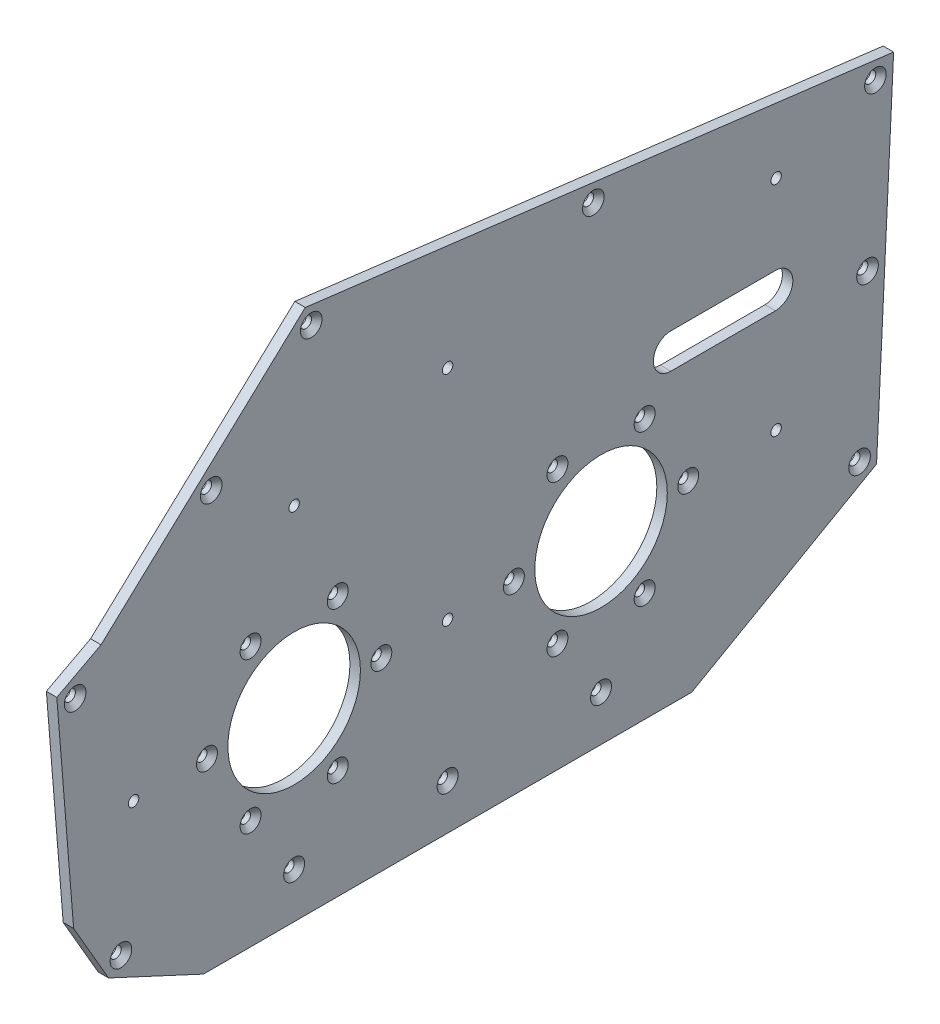
SolidWorks part; units mm, degrees
ref_plane "前视基准面" through (0, 0, 0) normal (0, 0, 1) x (1, 0, 0)
ref_plane "上视基准面" through (0, 0, 0) normal (0, 1, 0) x (1, 0, 0)
ref_plane "右视基准面" through (0, 0, 0) normal (1, 0, 0) x (0, 0, -1)
sketch "草图1" plane through (0, 0, 0) normal (1, 0, 0) x (0, 0, -1)
  line L0 (-82.7978, -47.6757) -> (57.2022, -47.6757)
  line L1 (-56.7978, 5.3243) -> (31.2022, 5.3243) construction
  line L2 (-12.7978, -47.6757) -> (-12.7978, 5.3243) construction
  line L3 (-81.3465, -44.5639) -> (329.9868, -44.5639) construction
  line L4 (-82.7978, -47.6757) -> (-110.0054, -35.0364)
  line L5 (-110.0054, -35.0364) -> (-120.0304, -17.7304)
  line L6 (-120.0304, -17.7304) -> (-124.8541, 42.0754)
  line L7 (-124.8541, 42.0754) -> (-112.1769, 48.7958)
  line L8 (-112.1769, 48.7958) -> (-53.6007, 103.2828)
  line L9 (-53.6007, 103.2828) -> (115.1062, 82.3551)
  line L10 (115.1062, 82.3551) -> (110.2084, -17.5249)
  line L11 (110.2084, -17.5249) -> (57.2022, -47.6757)
  line L12 (-56.7978, 5.3243) -> (-44.2978, 26.975) construction
  line L13 (-69.2978, 26.975) -> (-44.2978, 26.975) construction
  line L14 (31.2022, 5.3243) -> (43.7022, 26.975) construction
  line L15 (43.7022, 26.975) -> (18.7022, 26.975) construction
  line L16 (-12.7978, -47.6757) -> (-12.7978, -34.6757) construction
  line L17 (-12.7978, -34.6757) -> (-56.7978, -34.6757) construction
  line L18 (-12.7978, -34.6757) -> (31.2022, -34.6757) construction
  circle A0 centre (-56.7978, 5.3243) radius 19
  circle A1 centre (31.2022, 5.3243) radius 19
  circle A2 centre (-44.2978, 26.975) radius 1.5
  circle A3 centre (-69.2978, 26.975) radius 1.5
  circle A4 centre (-81.7978, 5.3243) radius 1.5
  circle A5 centre (-69.2978, -16.3263) radius 1.5
  circle A6 centre (-44.2978, -16.3263) radius 1.5
  circle A7 centre (-31.7978, 5.3243) radius 1.5
  circle A8 centre (43.7022, 26.975) radius 1.5
  circle A9 centre (56.2022, 5.3243) radius 1.5
  circle A10 centre (43.7022, -16.3263) radius 1.5
  circle A11 centre (18.7022, -16.3263) radius 1.5
  circle A12 centre (6.2022, 5.3243) radius 1.5
  circle A13 centre (18.7022, 26.975) radius 1.5
  circle A14 centre (-12.7978, -34.6757) radius 1.5
  circle A15 centre (-56.7978, -34.6757) radius 1.5
  circle A16 centre (31.2022, -34.6757) radius 1.5
  dimension "D2" = 38
  dimension "D3" = 38
  dimension "D23" = 3
  dimension "D26" = 6
  dimension "D27" = 3
  dimension "D29" = 3
  dimension "D32" = 3
  dimension "D33" = 3
  dimension "D1" = 140
  dimension "D4" = 88
  dimension "D5" = 53
  dimension "D6" = 155.083
  dimension "D7" = 30
  dimension "D8" = 145
  dimension "D9" = 20
  dimension "D10" = 154.528
  dimension "D11" = 60
  dimension "D12" = 113.317
  dimension "D13" = 14.3483
  dimension "D14" = 80
  dimension "D15" = 195
  dimension "D16" = 130
  dimension "D17" = 170
  dimension "D18" = 94.264
  dimension "D19" = 100
  dimension "D20" = 122.439
  dimension "D21" = 60.9814
  dimension "D22" = 25
  dimension "D25" = 25
  dimension "D28" = 13
  dimension "D30" = 44
  dimension "D31" = 44
  dimension "D24" = 6
extrude "凸台-拉伸1" add sketch "草图1" along normal blind 3
ref_plane "基准面1" through (13, 0, 0) normal (1, 0, 0) x (0, 0, -1)
sketch "草图2" plane through (13, 0, 0) normal (1, 0, 0) x (0, 0, -1)
  line L0 (-50.2042, 92.7848) -> (-106.3299, 40.5771)
  line L1 (-106.3299, 40.5771) -> (-114.3575, 36.3216)
  line L2 (-114.3575, 36.3216) -> (-110.2445, -14.6736)
  line L3 (-110.2445, -14.6736) -> (-102.9328, -27.2956)
  line L4 (-102.9328, -27.2956) -> (-80.5885, -37.6757)
  line L5 (-80.5885, -37.6757) -> (54.5571, -37.6757)
  line L6 (54.5571, -37.6757) -> (100.4894, -11.5486)
  line L7 (100.4894, -11.5486) -> (104.6636, 73.5738)
  line L8 (104.6636, 73.5738) -> (-50.2042, 92.7848)
  line L9 (-110.0054, -35.0364) -> (-82.7978, -47.6757)
  line L10 (-82.7978, -47.6757) -> (57.2022, -47.6757)
  line L11 (57.2022, -47.6757) -> (110.2084, -17.5249)
  line L12 (110.2084, -17.5249) -> (115.1062, 82.3551)
  line L13 (115.1062, 82.3551) -> (-53.6007, 103.2828)
  line L14 (-53.6007, 103.2828) -> (-112.1769, 48.7958)
  line L15 (-112.1769, 48.7958) -> (-124.8541, 42.0754)
  line L16 (-124.8541, 42.0754) -> (-120.0304, -17.7304)
  line L17 (-120.0304, -17.7304) -> (-110.0054, -35.0364)
  line L18 (-110.0054, -35.0364) -> (-82.7978, -47.6757)
  line L19 (-82.7978, -47.6757) -> (57.2022, -47.6757)
  line L20 (57.2022, -47.6757) -> (110.2084, -17.5249)
  line L21 (110.2084, -17.5249) -> (115.1062, 82.3551)
  line L22 (115.1062, 82.3551) -> (-53.6007, 103.2828)
  line L23 (-53.6007, 103.2828) -> (-112.1769, 48.7958)
  line L24 (-112.1769, 48.7958) -> (-124.8541, 42.0754)
  line L25 (-124.8541, 42.0754) -> (-120.0304, -17.7304)
  line L26 (-120.0304, -17.7304) -> (-110.0054, -35.0364)
  line L27 (-106.4691, -31.166) -> (-81.6932, -42.6757)
  line L28 (-81.6932, -42.6757) -> (55.8796, -42.6757)
  line L29 (55.8796, -42.6757) -> (105.3489, -14.5367)
  line L30 (105.3489, -14.5367) -> (109.8849, 77.9645)
  line L31 (109.8849, 77.9645) -> (-51.9024, 98.0338)
  line L32 (-51.9024, 98.0338) -> (-109.2534, 44.6864)
  line L33 (-109.2534, 44.6864) -> (-119.6058, 39.1985)
  line L34 (-119.6058, 39.1985) -> (-115.1374, -16.202)
  line L35 (-115.1374, -16.202) -> (-106.4691, -31.166)
  circle A0 centre (109.8849, 77.9645) radius 1.6
  circle A1 centre (105.3489, -14.5367) radius 1.6
  circle A3 centre (-106.4691, -31.166) radius 1.6
  circle A4 centre (-119.6058, 39.1985) radius 1.6
  circle A5 centre (-51.9024, 98.0338) radius 1.6
  circle A6 centre (28.9912, 87.9992) radius 1.6
  circle A7 centre (-80.5779, 71.3601) radius 1.6
  circle A8 centre (107.6169, 31.7139) radius 1.6
  dimension "D1" = 0
  dimension "D2" = 10
  dimension "D3" = 5
extrude "切除-拉伸1" cut sketch "草图2" against normal blind 77 contours L31 A6 | L31 A6 | L32 A5 L31 | L30 A0 L31 | L31 A0 L30 | L30 A8 | L30 A8 | L29 A1 L30 | L30 A1 L29 | L27 A3 L35 | L35 A3 L27 | L34 A4 L33 | L33 A4 L34 | L32 A7 | L32 A7
chamfer "倒角1" distance 1.5 angle 45 23 edges at (3, 77.9645, -111.4849) (3, 31.7139, -109.2169) (3, -14.5367, -106.9489) (3, 5.3243, -57.7022) (3, 5.3243, -7.7022) (3, -16.3263, -45.2022) (3, -16.3263, -20.2022) (3, -34.6757, -32.7022) (3, -34.6757, 11.2978) (3, -34.6757, 55.2978) (3, -31.166, 104.8691) (3, 71.3601, 78.9779) (3, 39.1985, 118.0058) (3, -16.3263, 67.7978) (3, -16.3263, 42.7978) (3, 5.3243, 30.2978) (3, 5.3243, 80.2978) (3, 26.975, 67.7978) (3, 26.975, 42.7978) (3, 26.975, -45.2022) (3, 26.975, -20.2022) (3, 87.9992, -30.5912) (3, 98.0338, 50.3024)
sketch "草图3" plane through (3, 0, 0) normal (1, 0, 0) x (0, 0, -1)
  line L0 (31.2022, 5.3243) -> (51.2022, 40.0495)
  line L1 (51.2022, 40.0495) -> (81.2022, 40.0495) construction
  line L2 (51.2022, 45.0495) -> (81.2022, 45.0495)
  line L3 (51.2022, 35.0495) -> (81.2022, 35.0495)
  arc A0 (51.2022, 45.0495) -> (51.2022, 35.0495) centre (51.2022, 40.0495) ccw
  arc A1 (81.2022, 35.0495) -> (81.2022, 45.0495) centre (81.2022, 40.0495) ccw
  point P3 (66.2022, 40.0495)
extrude "切除-拉伸2" cut sketch "草图3" against normal blind 10
sketch "草图4" plane through (3, 0, 0) normal (1, 0, 0) x (0, 0, -1)
  line L0 (-56.7978, 5.3243) -> (31.2022, 5.3243)
  line L1 (-12.7978, 3.8243) -> (-12.7978, 82.3718)
  line L2 (-80.2978, 5.3243) -> (-108.4186, 5.3243)
  line L3 (54.7022, 5.3243) -> (97.6281, 5.3243)
  circle A0 centre (-12.7978, 5.3243) radius 1.5
  circle A1 centre (-12.7978, 67.8864) radius 1.5
  circle A2 centre (-81.7978, 5.3243) radius 1.5 construction
  circle A3 centre (-102.8483, 5.3243) radius 1.5
  circle A5 centre (56.2022, 5.3243) radius 1.5 construction
  circle A6 centre (81.4075, 5.3243) radius 1.5
  circle A7 centre (-56.7978, 55.6501) radius 1.5
  circle A8 centre (81.4075, 67.8864) radius 1.5
extrude "切除-拉伸3" cut sketch "草图4" against normal blind 10 contours L2 A3 | A8 | A7 | A1 | A0 | A6
ref_plane "基准面3" through (-10, 0, 0) normal (-1, 0, 0) x (0, 0, 1)
sketch "草图5" plane through (0, 0, 0) normal (-1, 0, 0) x (0, 0, 1)
  line L0 (51.9024, 98.0338) -> (-109.8849, 77.9645)
  line L1 (-109.8849, 77.9645) -> (-105.3489, -14.5367)
  line L2 (-105.3489, -14.5367) -> (-55.8796, -42.6757)
  line L3 (-55.8796, -42.6757) -> (81.6932, -42.6757)
  line L4 (81.6932, -42.6757) -> (106.4691, -31.166)
  line L5 (106.4691, -31.166) -> (115.1374, -16.202)
  line L6 (115.1374, -16.202) -> (119.6058, 39.1985)
  line L7 (119.6058, 39.1985) -> (109.2534, 44.6864)
  line L8 (109.2534, 44.6864) -> (51.9024, 98.0338)
  line L9 (82.7978, -47.6757) -> (110.0054, -35.0364)
  line L10 (110.0054, -35.0364) -> (120.0304, -17.7304)
  line L11 (120.0304, -17.7304) -> (124.8541, 42.0754)
  line L12 (124.8541, 42.0754) -> (112.1769, 48.7958)
  line L13 (112.1769, 48.7958) -> (53.6007, 103.2828)
  line L14 (53.6007, 103.2828) -> (-115.1062, 82.3551)
  line L15 (-115.1062, 82.3551) -> (-110.2084, -17.5249)
  line L16 (-110.2084, -17.5249) -> (-57.2022, -47.6757)
  line L17 (-57.2022, -47.6757) -> (82.7978, -47.6757)
  line L18 (82.7978, -47.6757) -> (110.0054, -35.0364)
  line L19 (110.0054, -35.0364) -> (120.0304, -17.7304)
  line L20 (120.0304, -17.7304) -> (124.8541, 42.0754)
  line L21 (124.8541, 42.0754) -> (112.1769, 48.7958)
  line L22 (112.1769, 48.7958) -> (53.6007, 103.2828)
  line L23 (53.6007, 103.2828) -> (-115.1062, 82.3551)
  line L24 (-115.1062, 82.3551) -> (-110.2084, -17.5249)
  line L25 (-110.2084, -17.5249) -> (-57.2022, -47.6757)
  line L26 (-57.2022, -47.6757) -> (82.7978, -47.6757)
  line L27 (-31.2022, 5.3243) -> (-43.7022, 26.975)
  line L28 (-43.7022, 26.975) -> (-51.2022, 40.0495)
  dimension "D1" = 0
  dimension "D2" = 5
